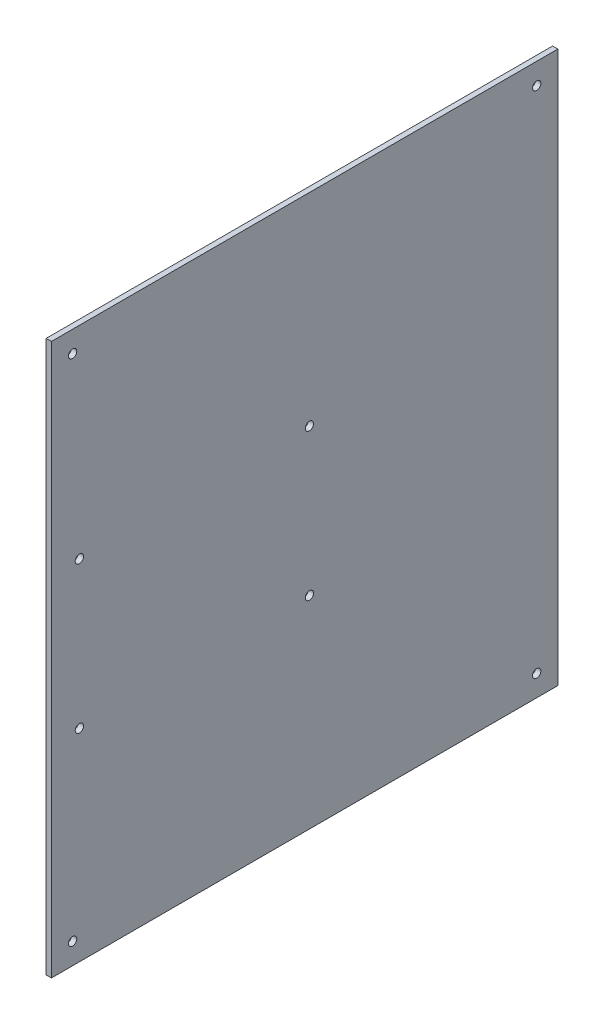
SolidWorks part; units mm, degrees
ref_plane "Front Plane" through (0, 0, 0) normal (1, 0, 0) x (0, 1, 0)
ref_plane "Top Plane" through (0, 0, 0) normal (0, 0, 1) x (0, 1, 0)
ref_plane "Right Plane" through (0, 0, 0) normal (0, 1, 0) x (-1, 0, 0)
sketch "Sketch1" plane through (0, 0, 0) normal (1, 0, 0) x (0, 1, 0)
  line L0 (0, -151.892) -> (0, 49848.108) construction
  line L1 (-82.677, -151.892) -> (82.677, -151.892)
  line L2 (-82.677, -151.892) -> (-82.677, 0)
  line L3 (-82.677, 0) -> (82.677, 0)
  line L4 (82.677, -151.892) -> (82.677, 0)
  circle A1 centre (22, -77.382) radius 1.25
  circle A2 centre (22, -8.382) radius 1.25
  circle A3 centre (76.327, -6.35) radius 1.25
  circle A4 centre (76.327, -145.542) radius 1.25
  circle A5 centre (-22, -77.382) radius 1.25
  circle A6 centre (-76.327, -145.542) radius 1.25
  circle A7 centre (-76.327, -6.35) radius 1.25
  circle A8 centre (-22, -8.382) radius 1.25
  point P20 (0, -151.892)
  dimension "D1" = 2.5
extrude "Boss-Extrude1" add sketch "Sketch1" along normal blind 1.5823 contours L1 L0 L3 L2 A8 A6 A5 A7 | L0 L1 L4 L3 A4 A3 A2 A1
